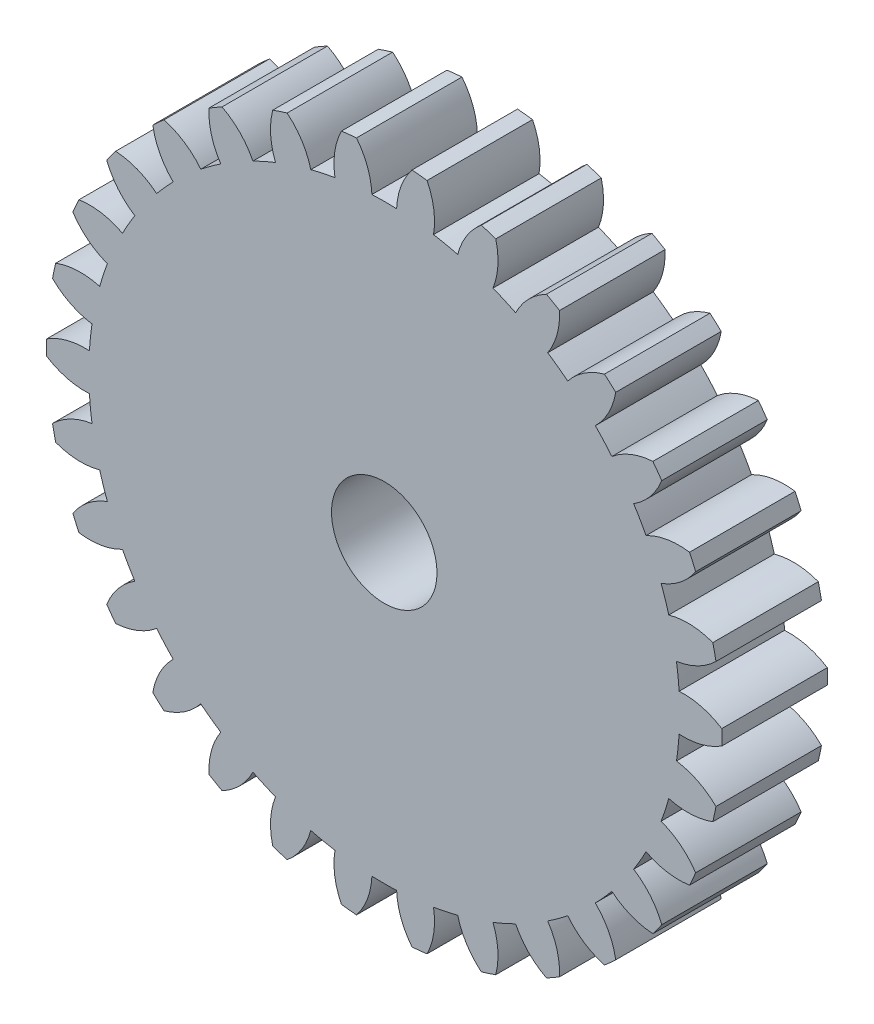
SolidWorks part; units mm, degrees
material "ABS"
ref_plane "Front Plane" through (0, 0, 0) normal (0, 0, 1) x (1, 0, 0)
ref_plane "Top Plane" through (0, 0, 0) normal (0, 1, 0) x (1, 0, 0)
ref_plane "Right Plane" through (0, 0, 0) normal (1, 0, 0) x (0, 0, -1)
sketch "Sketch1" plane through (0, 0, 0) normal (0, 0, 1) x (1, 0, 0)
  circle A0 centre (0, 0) radius 20.32
  dimension "D1" = 40.64
extrude "Outer Circle" add sketch "Sketch1" along normal blind 6.35
sketch "Sketch2" plane through (0, 0, 6.35) normal (0, 0, 1) x (1, 0, 0)
  line L0 (0.9984, 19.05) -> (-0.9984, 19.05) construction
  line L1 (2.9842, 18.8413) -> (0.9984, 19.05) construction
  line L2 (0, 19.05) -> (0, 0) construction
  line L3 (0, 0) -> (1.9913, 18.9456) construction
  line L4 (-1.442, 20.2688) -> (0, 16.307) construction
  line L5 (0, 16.307) -> (1.442, 20.2688) construction
  line L6 (-0.7438, 17.7644) -> (0, 0) construction
  circle A0 centre (0, 0) radius 17.78 construction
  circle A1 centre (0, 0) radius 19.05 construction
  arc A2 (-0.7438, 17.7644) -> (0.7438, 17.7644) centre (0, 0) cw
  arc A3 (-1.671, 20.2512) -> (1.671, 20.2512) centre (0, 0) cw
  circle A4 centre (0, 0) radius 20.32 construction
  arc A5 (-1.671, 20.2512) -> (-0.7438, 17.7644) centre (-5.0227, 17.5853) cw
  arc A6 (0.7438, 17.7644) -> (1.671, 20.2512) centre (5.0227, 17.5853) cw
  point P7 (0, 19.05)
  point P10 (1.9913, 18.9456)
  point P17 (0, 17.78)
  point P19 (0, 20.32)
  dimension "D1" = 35.56
  dimension "D2" = 38.1
  dimension "D3" = 6
  dimension "D4" = 20
extrude "Tooth Cut" cut sketch "Sketch2" against normal through all
pattern_circular "Teeth Pattern" count 30 over 360 about axis through (0, 0, 0) along (0, 0, 1) of "Tooth Cut"
ref_plane "Plane1" through (0, 0, 3.175) normal (0, 0, 1) x (1, 0, 0)
sketch "Pitch Diameter" plane through (0, 0, 3.175) normal (0, 0, 1) x (1, 0, 0)
  circle A0 centre (0, 0) radius 19.05 construction
  circle A1 centre (0, 0) radius 19.05
sketch "Sketch3" plane through (0, 0, 6.35) normal (0, 0, 1) x (1, 0, 0)
  circle A0 centre (0, 0) radius 3.175
  dimension "D1" = 6.35
extrude "Cut-Extrude1" cut sketch "Sketch3" against normal through all
equation "\"No. of Teeth\"= 30"
equation "\"Module\"= 1 / 20'Inverse of Pitch"
equation "\"D1@Sketch1\"=(\"No. of Teeth\"+2)*\"Module\""
equation "\"D1@Sketch2\"=(\"No. of Teeth\"-2)*\"Module\""
equation "\"D2@Sketch2\"= \"No. of Teeth\" * \"Module\"'Pitch Diameter"
equation "\"D3@Sketch2\"=180/\"No. of Teeth\""
equation "\"D1@Teeth Pattern\" = \"No. of Teeth\""
